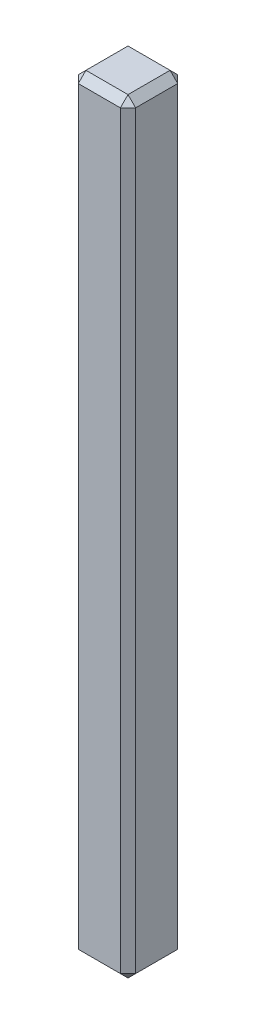
SolidWorks part; units mm, degrees
ref_plane "Front Plane" through (0, 0, 0) normal (0, 0, 1) x (1, 0, 0)
ref_plane "Top Plane" through (0, 0, 0) normal (0, 1, 0) x (1, 0, 0)
ref_plane "Right Plane" through (0, 0, 0) normal (1, 0, 0) x (0, 0, -1)
sketch "Sketch1" plane through (0, 0, 0) normal (0, 1, 0) x (1, 0, 0)
  line L1 (0, 0) -> (15, 0)
  line L2 (0, 0) -> (0, 15)
  line L3 (0, 15) -> (15, 15)
  line L4 (15, 0) -> (15, 15)
  dimension "D1" = 15
  dimension "D2" = 15
extrude "Boss-Extrude1" add sketch "Sketch1" along normal blind 200
chamfer "Chamfer1" distance 2 angle 45 12 edges at (15, 0, -7.5) (0, 0, -7.5) (15, 100, -15) (7.5, 0, -15) (0, 100, -15) (0, 100, 0) (7.5, 0, 0) (15, 100, 0) (7.5, 200, -15) (15, 200, -7.5) (7.5, 200, 0) (0, 200, -7.5)
